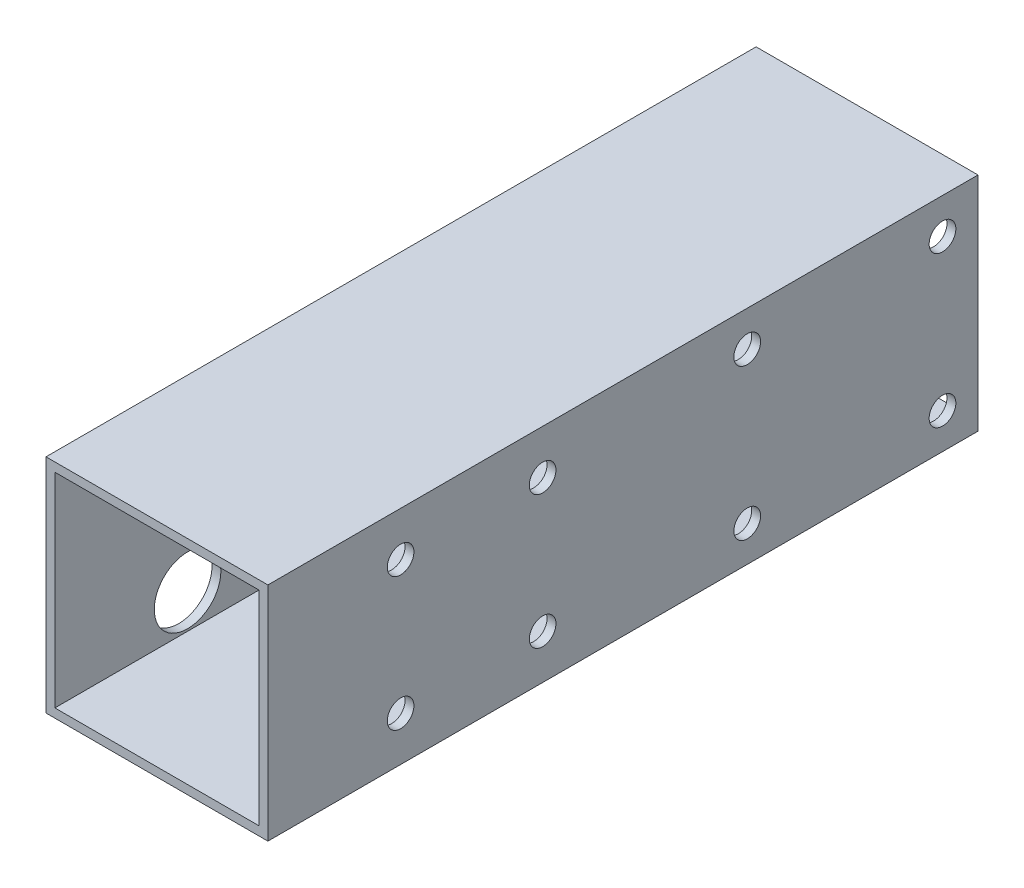
SolidWorks part; units mm, degrees
material "6061 合金"
ref_plane "前视基准面" through (0, 0, 0) normal (0, 0, 1) x (1, 0, 0)
ref_plane "上视基准面" through (0, 0, 0) normal (0, 1, 0) x (1, 0, 0)
ref_plane "右视基准面" through (0, 0, 0) normal (1, 0, 0) x (0, 0, -1)
sketch "草图1" plane through (0, 0, 0) normal (0, 0, 1) x (1, 0, 0)
  line L0 (-11.5, -11.5) -> (-11.5, 11.5)
  line L1 (-12.5, -12.5) -> (12.5, -12.5)
  line L2 (-12.5, -12.5) -> (-12.5, 12.5)
  line L3 (-12.5, 12.5) -> (12.5, 12.5)
  line L4 (12.5, -12.5) -> (12.5, 12.5)
  line L5 (0, 12.5) -> (0, -12.5) construction
  line L6 (-12.5, 0) -> (12.5, 0) construction
  line L7 (-11.5, 11.5) -> (11.5, 11.5)
  line L8 (11.5, -11.5) -> (11.5, 11.5)
  line L9 (-11.5, -11.5) -> (11.5, -11.5)
  point P0 (0, 0)
  dimension "D1" = 25
  dimension "D2" = 1
extrude "凸台-拉伸1" add sketch "草图1" along normal mid plane 80
sketch "草图3" plane through (12.5, 0, 0) normal (1, 0, 0) x (0, 0, -1)
  line L0 (0, 0) -> (180, 0) construction
  circle A0 centre (180, 0) radius 2
  circle A1 centre (150, 0) radius 2
  dimension "D2" = 4
  dimension "D1" = 180
  dimension "D3" = 30
extrude "切除-拉伸2" [suppressed] cut sketch "草图3" against normal blind 40
sketch "草图4" plane through (11.5, 0, 0) normal (-1, 0, 0) x (0, 0, 1)
  circle A0 centre (25.05, -7.5) radius 1.5 construction
  circle A1 centre (25.05, 7.5) radius 1.5 construction
  circle A2 centre (9.05, 7.5) radius 1.5 construction
  circle A3 centre (9.05, -7.5) radius 1.5 construction
  circle A4 centre (25.05, -7.5) radius 1.5
  circle A5 centre (25.05, 7.5) radius 1.5
  circle A6 centre (9.05, 7.5) radius 1.5
  circle A7 centre (9.05, -7.5) radius 1.5
extrude "切除-拉伸3" cut sketch "草图4" against normal blind 10
sketch "草图5" [suppressed] plane through (0, 12.5, 0) normal (0, 1, 0) x (1, 0, 0)
  line L0 (0, 178.55) -> (0, 148.55) construction
  line L1 (0, 178.55) -> (0, 185) construction
  line L2 (12.5, 185) -> (-12.5, 185) construction
  circle A2 centre (0, 178.55) radius 2
  circle A3 centre (0, 148.55) radius 2
  dimension "D3" = 4
  dimension "D1" = 6.45
  dimension "D2" = 30
extrude "切除-拉伸4" [suppressed] cut sketch "草图5" against normal blind 70
sketch "草图6" [suppressed] plane through (11.5, 0, 0) normal (-1, 0, 0) x (0, 0, 1)
  circle A0 centre (209, 0) radius 1.5 construction
  circle A1 centre (232.5, 0) radius 1.5 construction
  circle A2 centre (256, 0) radius 1.5 construction
  circle A3 centre (209, 0) radius 1.5
  circle A4 centre (232.5, 0) radius 1.5
  circle A5 centre (256, 0) radius 1.5
extrude "切除-拉伸5" [suppressed] cut sketch "草图6" against normal blind 10
sketch "草图7" [suppressed] plane through (0, 12.5, 0) normal (0, 1, 0) x (1, 0, 0)
  circle A0 centre (0, -214) radius 1.5 construction
  circle A1 centre (0, -251) radius 1.5 construction
  circle A2 centre (0, -214) radius 1.5
  circle A3 centre (0, -251) radius 1.5
extrude "切除-拉伸6" [suppressed] cut sketch "草图7" against normal blind 98
sketch "草图8" [suppressed] plane through (0, -11.5, 0) normal (0, 1, 0) x (1, 0, 0)
  circle A0 centre (0, 252.5) radius 1.5 construction
  circle A1 centre (0, 252.5) radius 1.5
extrude "切除-拉伸7" [suppressed] cut sketch "草图8" against normal blind 10
pattern_linear "阵列(线性)1" [suppressed] count 24 spacing 20
sketch "草图9" [suppressed] plane through (0, 11.5, 0) normal (0, -1, 0) x (1, 0, 0)
  line L0 (0, -212.5) -> (0, -232.5) construction
  line L1 (5, -212.5) -> (5, -232.5)
  line L2 (-5, -212.5) -> (-5, -232.5)
  arc A0 (5, -212.5) -> (-5, -212.5) centre (0, -212.5) ccw
  arc A1 (-5, -232.5) -> (5, -232.5) centre (0, -232.5) ccw
  point P4 (0, -222.5)
  dimension "D1" = 5
extrude "切除-拉伸8" [suppressed] cut sketch "草图9" against normal blind 10
pattern_linear "阵列(线性)2" [suppressed] count 7 spacing 60
sketch "草图10" [suppressed] plane through (0, 11.5, 0) normal (0, -1, 0) x (1, 0, 0)
  circle A0 centre (0, 187.5) radius 5
  dimension "D1" = 10
extrude "切除-拉伸9" [suppressed] cut sketch "草图10" against normal blind 10
sketch "草图11" [suppressed] plane through (-11.5, 0, 0) normal (1, 0, 0) x (0, 0, -1)
  circle A0 centre (-209, 0) radius 1.5 construction
  circle A1 centre (-256, 0) radius 1.5 construction
  circle A2 centre (-232.5, 0) radius 1.5 construction
  circle A3 centre (-209, 0) radius 1.5
  circle A4 centre (-256, 0) radius 1.5
  circle A5 centre (-232.5, 0) radius 1.5
extrude "切除-拉伸10" [suppressed] cut sketch "草图11" against normal blind 51
sketch "草图12" [suppressed] plane through (12.5, 0, 0) normal (1, 0, 0) x (0, 0, -1)
  circle A0 centre (-67.9, -7.5) radius 1.5 construction
  circle A1 centre (-87.9, -7.5) radius 1.5 construction
  circle A2 centre (-67.9, 7.5) radius 1.5 construction
  circle A3 centre (-87.9, 7.5) radius 1.5 construction
  circle A4 centre (-67.9, -7.5) radius 1.5
  circle A5 centre (-87.9, -7.5) radius 1.5
  circle A6 centre (-67.9, 7.5) radius 1.5
  circle A7 centre (-87.9, 7.5) radius 1.5
  circle A8 centre (25, 7.5) radius 1.525 construction
  circle A9 centre (25, -7.5) radius 1.525 construction
  circle A10 centre (0, -7.5) radius 1.525 construction
  circle A11 centre (0, 7.5) radius 1.525 construction
  circle A12 centre (-25, -7.5) radius 1.525 construction
  circle A13 centre (-25, 7.5) radius 1.525 construction
  circle A14 centre (25, 7.5) radius 1.525
  circle A15 centre (25, -7.5) radius 1.525
  circle A16 centre (0, -7.5) radius 1.525
  circle A17 centre (0, 7.5) radius 1.525
  circle A18 centre (-25, -7.5) radius 1.525
  circle A19 centre (-25, 7.5) radius 1.525
  circle A20 centre (87.9, -7.5) radius 1.5 construction
  circle A21 centre (87.9, 7.5) radius 1.5 construction
  circle A22 centre (67.9, -7.5) radius 1.5 construction
  circle A23 centre (67.9, 7.5) radius 1.5 construction
  circle A24 centre (87.9, -7.5) radius 1.5
  circle A25 centre (87.9, 7.5) radius 1.5
  circle A26 centre (67.9, -7.5) radius 1.5
  circle A27 centre (67.9, 7.5) radius 1.5
extrude "切除-拉伸11" [suppressed] cut sketch "草图12" against normal mid plane 113
sketch "草图13" [suppressed] plane through (0, 12.5, 0) normal (0, 1, 0) x (1, 0, 0)
  circle A0 centre (-7.5, -160) radius 1.5 construction
  circle A1 centre (-7.5, -180) radius 1.5 construction
  circle A2 centre (7.5, -160) radius 1.5 construction
  circle A3 centre (7.5, -180) radius 1.5 construction
  circle A4 centre (-7.5, -160) radius 1.5
  circle A5 centre (-7.5, -180) radius 1.5
  circle A6 centre (7.5, -160) radius 1.5
  circle A7 centre (7.5, -180) radius 1.5
extrude "切除-拉伸12" [suppressed] cut sketch "草图13" against normal mid plane 113
sketch "草图14" [suppressed] plane through (0, 12.5, 0) normal (0, 1, 0) x (1, 0, 0)
  circle A0 centre (0, 132.5) radius 1.75 construction
  circle A1 centre (0, 132.5) radius 1.75 construction
  circle A2 centre (0, 132.5) radius 1.5
  dimension "D1" = 3
extrude "切除-拉伸13" [suppressed] cut sketch "草图14" against normal blind 70
pattern_linear "阵列(线性)3" [suppressed] count 15 spacing 20
sketch "草图15" [suppressed] plane through (-11.5, 0, 0) normal (1, 0, 0) x (0, 0, -1)
  circle A0 centre (15, 0) radius 1.25 construction
  circle A1 centre (-170, 0) radius 1.25 construction
  circle A2 centre (15, 0) radius 1.25 construction
  circle A3 centre (-170, 0) radius 1.25 construction
  circle A4 centre (-170, 0) radius 1.5
  circle A5 centre (15, 0) radius 1.5
  dimension "D1" = 3
extrude "切除-拉伸14" [suppressed] cut sketch "草图15" against normal mid plane 110
sketch "草图16" [suppressed] plane through (12.5, 0, 0) normal (1, 0, 0) x (0, 0, -1)
  line L0 (-126, 12.5) -> (-129, 12.5) construction
  line L1 (-146, 12.5) -> (-149, 12.5) construction
  line L2 (-126, 12.5) -> (-129, 12.5) construction
  line L3 (-146, 12.5) -> (-149, 12.5) construction
  line L4 (-170, 0) -> (-127.5, 0) construction
  line L5 (-127.5, 0) -> (-127.5, 12.5) construction
  line L6 (-147.5, 12.5) -> (-147.5, 0) construction
  line L7 (-147.5, 0) -> (-127.5, 0) construction
  line L10 (-147.5, 5) -> (-127.5, 5)
  line L11 (-147.5, -5) -> (-127.5, -5)
  arc A2 (-147.5, 5) -> (-147.5, -5) centre (-147.5, 0) ccw
  arc A3 (-127.5, -5) -> (-127.5, 5) centre (-127.5, 0) ccw
  point P11 (-137.5, 0)
  dimension "D1" = 5
extrude "切除-拉伸15" [suppressed] cut sketch "草图16" against normal mid plane 110
pattern_linear "阵列(线性)4" [suppressed] count 15 spacing 60
sketch "草图17" plane through (-12.5, 0, 0) normal (-1, 0, 0) x (0, 0, 1)
  circle A0 centre (25.05, 7.5) radius 3.75
  circle A1 centre (9.05, 7.5) radius 3.75
  circle A2 centre (25.05, -7.5) radius 3.75
  circle A3 centre (9.05, -7.5) radius 3.75
  dimension "D1" = 7.5
extrude "切除-拉伸16" cut sketch "草图17" against normal up to surface (1 mm away) up to face at (-11.5, 0, 0)
sketch "草图18" plane through (-12.5, 0, 0) normal (-1, 0, 0) x (0, 0, 1)
  circle A0 centre (-36, 8.5) radius 1.505 construction
  circle A1 centre (-14, 8.5) radius 1.505 construction
  circle A2 centre (-14, -8.5) radius 1.505 construction
  circle A3 centre (-36, -8.5) radius 1.505 construction
  circle A4 centre (-36, 8.5) radius 1.505
  circle A5 centre (-14, 8.5) radius 1.505
  circle A6 centre (-14, -8.5) radius 1.505
  circle A7 centre (-36, -8.5) radius 1.505
extrude "切除-拉伸17" cut sketch "草图18" against normal up to surface (25 mm away) up to face at (12.5, -9, 9.05)
